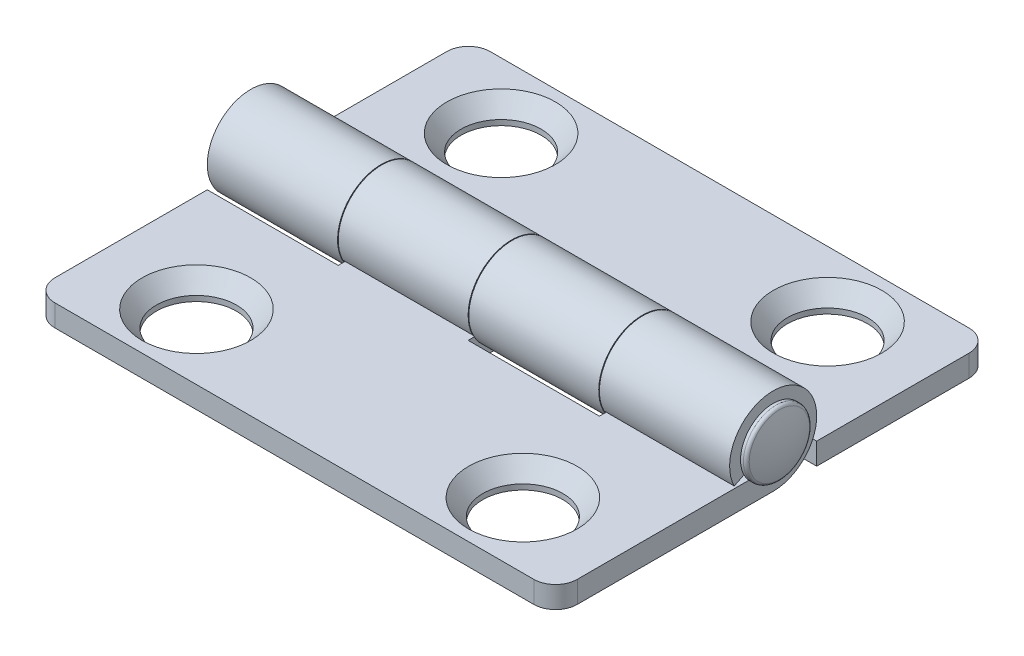
SolidWorks part; units mm, degrees
ref_plane "Front Plane" through (0, 0, 0) normal (0, 0, 1) x (1, 0, 0)
ref_plane "Top Plane" through (0, 0, 0) normal (0, 1, 0) x (1, 0, 0)
ref_plane "Right Plane" through (0, 0, 0) normal (1, 0, 0) x (0, 0, -1)
sketch "Sketch1" plane through (0, 0, 0) normal (0, 1, 0) x (1, 0, 0)
  line L0 (-19.05, 0) -> (19.05, 0) construction
  line L1 (-19.05, -15.875) -> (-19.05, 15.875) construction
  line L2 (11.9062, 11.1125) -> (11.9062, -11.1125) construction
  line L3 (-11.9062, -15.875) -> (11.9063, -15.875) construction
  line L4 (0, 0) -> (0, -15.875) construction
  line L5 (11.9062, -8.1915) -> (11.9063, -14.0335) construction
  line L7 (-11.9062, 11.1125) -> (11.9062, 11.1125) construction
  line L8 (-11.9062, 11.1125) -> (-11.9062, -11.1125) construction
  line L9 (-11.9062, -11.1125) -> (11.9062, -11.1125) construction
  line L10 (11.9062, 11.1125) -> (11.9062, -11.1125) construction
  line L11 (14.8273, -11.1125) -> (8.9853, -11.1125) construction
  line L12 (-11.9062, 11.1125) -> (11.9062, -11.1125) construction
  line L13 (-11.9062, -11.1125) -> (11.9062, 11.1125) construction
  circle A0 centre (11.9062, -11.1125) radius 3.9624 construction
  point P4 (0, 0)
  point P8 (-19.05, 0)
  point P17 (-9.525, 0)
  point P21 (11.9062, -11.1125)
  point P25 (11.9063, 0)
  point P26 (11.9062, -11.1125)
  point P38 (11.9062, -11.1125)
  dimension "Screw Head Diameter" = 7.9248
  dimension "Door Leaf Height" = 38.1
  dimension "Overall Width" = 31.75
  dimension "Hole Spacing" = 23.8125
  dimension "Knuckle Length" = 9.525
  dimension "Hole Diameter" = 5.842
  dimension "Hole Spacing 2" = 22.225
  dimension "Frame Leaf Height" = 38.1
  dimension "Door Leaf Width" = 15.875
  dimension "Frame Leaf Width" = 15.875
sketch "Sketch2" plane through (0, 0, 0) normal (1, 0, 0) x (0, 0, -1)
  line L2 (0, -3.175) -> (0, -1.5875) construction
  line L4 (0, 1.5875) -> (0, -1.5875) construction
  point P8 (0, 0)
  dimension "Leaf Thickness" = 1.5875
  dimension "Pin Diameter" = 3.175
sketch "Sketch3" plane through (0, 0, 0) normal (1, 0, 0) x (0, 0, -1)
  line L3 (0, 0) -> (-3.175, -1.5875) construction
  line L4 (0, -3.175) -> (-15.875, -3.175)
  line L5 (-15.875, -3.175) -> (-15.875, -1.5875)
  line L7 (-15.875, -1.5875) -> (0, -1.5875)
  line L8 (-15.875, 0) -> (15.875, 0) construction
  line L9 (-1.4199, -0.71) -> (-2.8398, -1.4199)
  line L11 (-3.175, 0) -> (-3.175, -1.5875) construction
  circle A4 centre (0, 0) radius 1.5875 construction
  circle A5 centre (0, 0) radius 3.175 construction
  arc A8 (-1.4199, -0.71) -> (0, -1.5875) centre (0, 0) cw
  arc A9 (-2.8398, -1.4199) -> (0, -3.175) centre (0, 0) cw
  point P0 (-2.8398, -1.4199)
  point P13 (-1.4199, -0.71)
extrude "Boss-Extrude1" add sketch "Sketch3" along normal mid plane 38.1
sketch "Sketch4" plane through (0, 0, 0) normal (0, 1, 0) x (1, 0, 0)
  line L0 (-19.05, -3.175) -> (19.05, -3.175) construction
  line L1 (-19.05, -3.175) -> (19.05, -3.175) construction
  line L2 (19.05, 3.175) -> (-19.05, 3.175) construction
  line L3 (19.05, 3.175) -> (-19.05, 3.175) construction
  line L4 (0, -3.175) -> (0, 3.175)
  line L6 (0, 3.175) -> (9.525, 3.175)
  line L7 (9.525, -3.175) -> (0, -3.175)
  line L8 (9.525, 3.175) -> (9.525, -3.175)
  point P8 (-9.525, 0)
  dimension "D1" = 9.525
extrude "Cut-Extrude1" cut sketch "Sketch4" against normal through all both and the other way through all
pattern_linear "LPattern1" count 2 spacing 19.05 along (-1, 0, 0) of "Cut-Extrude1"
sketch "Sketch5" plane through (0, -1.5875, 0) normal (0, 1, 0) x (1, 0, 0)
  line L0 (-9.525, -3.175) -> (0, -3.175) construction
  line L1 (-9.525, 3.175) -> (-9.4996, 3.175)
  line L2 (-9.525, 3.175) -> (-9.525, -3.175)
  line L3 (-9.525, -3.175) -> (-9.4996, -3.175)
  line L4 (-9.4996, 3.175) -> (-9.4996, -3.175)
  line L5 (9.525, 3.175) -> (9.525, -3.175) construction
  line L6 (0, 3.175) -> (-0.0254, 3.175)
  line L7 (0, 3.175) -> (0, -3.175)
  line L8 (0, -3.175) -> (-0.0254, -3.175)
  line L9 (-0.0254, 3.175) -> (-0.0254, -3.175)
  line L10 (9.525, 3.175) -> (9.5504, 3.175)
  line L11 (9.525, 3.175) -> (9.525, -3.175)
  line L12 (9.525, -3.175) -> (9.5504, -3.175)
  line L13 (9.5504, 3.175) -> (9.5504, -3.175)
  line L14 (9.525, -3.175) -> (19.05, -3.175) construction
  line L15 (19.05, 3.175) -> (9.525, 3.175) construction
  dimension "D1" = 0.0254
extrude "Cut-Extrude2" cut sketch "Sketch5" against normal through all both and the other way through all
sketch "Sketch6" plane through (0, -1.5875, 0) normal (0, 1, 0) x (1, 0, 0)
  line L0 (11.9062, -11.1125) -> (-11.9062, -11.1125) construction
  line L1 (11.9062, -11.1125) -> (11.9063, -15.875) construction
  line L2 (-11.9062, -11.1125) -> (-11.9062, -15.875) construction
  line L3 (11.9062, -11.1125) -> (13.3668, -13.6422) construction
  circle A0 centre (11.9062, -11.1125) radius 2.921
  circle A3 centre (-11.9062, -11.1125) radius 2.921
  point P7 (13.3668, -13.6422)
  dimension "D1" = 30
extrude "Cut-Extrude3" cut sketch "Sketch6" against normal through all
sketch "Sketch7" plane through (0, -1.5875, 0) normal (0, 1, 0) x (1, 0, 0)
  circle A0 centre (-11.9062, -11.1125) radius 3.9624
  circle A1 centre (11.9062, -11.1125) radius 3.9624
  circle A2 centre (11.9062, -11.1125) radius 3.9624 construction
extrude "Cut-Extrude4" cut sketch "Sketch7" against normal through all draft 41
fillet "Fillet1" radius 1.5875 2 edges at (19.05, -2.3813, 15.875) (-19.05, -2.3813, 15.875)
pattern_circular "CirPattern1" count 2 over 360 about axis through (0, 0, 0) along (0, 1, 0) of bodies 111 107
sketch "Sketch8" plane through (0, 0, 0) normal (1, 0, 0) x (0, 0, -1)
  circle A0 centre (0, 0) radius 1.5875
  dimension "D1" = 3.175
extrude "Boss-Extrude2" add sketch "Sketch8" along normal mid plane 38.1 separate body
sketch "Sketch9" plane through (0, 0, 0) normal (0, 0, 1) x (1, 0, 0)
  line L0 (-19.05, 0) -> (19.05, 0) construction
  line L2 (19.05, 2.3813) -> (19.05, -2.3813) construction
  line L3 (19.05, 0) -> (19.8437, 0) construction
  line L7 (19.05, 2.3813) -> (19.05, 0)
  line L8 (19.05, 0) -> (19.8437, 0)
  line L9 (19.05, -1.5875) -> (19.05, -3.175) construction
  line L10 (-19.05, -2.3813) -> (19.05, -2.3813) construction
  line L12 (19.05, 2.3813) -> (19.263, 2.3813)
  line L13 (19.05, 1.5875) -> (19.05, 3.175) construction
  line L15 (0, -2.3813) -> (0, 3.175) construction
  line L17 (-19.05, 0) -> (-19.8437, 0) construction
  line L18 (-19.05, 2.3813) -> (-19.263, 2.3813)
  line L19 (-19.05, 0) -> (-19.8437, 0)
  line L20 (-19.05, 2.3813) -> (-19.05, 0)
  line L21 (19.05, 1.5875) -> (9.5504, 1.5875) construction
  line L22 (19.05, 3.175) -> (9.5504, 3.175) construction
  line L23 (9.4996, 3.175) -> (0.0254, 3.175) construction
  arc A0 (19.05, 2.3813) -> (19.05, -2.3813) centre (15.875, 0) cw construction
  arc A4 (19.5053, 2.2035) -> (19.8437, 0) centre (12.5016, 0) cw
  arc A5 (19.263, 2.3813) -> (19.5053, 2.2035) centre (19.263, 2.1273) cw
  arc A6 (-19.263, 2.3813) -> (-19.5053, 2.2035) centre (-19.263, 2.1273) ccw
  arc A7 (-19.5053, 2.2035) -> (-19.8437, 0) centre (-12.5016, 0) ccw
  point P12 (19.05, 0)
  point P20 (19.4469, 0)
  point P29 (19.4469, 2.3813)
  point P34 (-19.4469, 2.3813)
  point P35 (-19.4469, 0)
  point P36 (19.05, 2.3813)
  dimension "D2" = 0.254
  dimension "D1" = 0.7937
revolve "Revolve1" add sketch "Sketch9" angle 360 about L0
equation "\"D1@Boss-Extrude1\" = \"Door Leaf Height@Sketch1\""
equation "\"D1@Sketch4\"=\"Knuckle Length@Sketch1\""
equation "\"D3@LPattern1\"=\"Knuckle Length@Sketch1\"*2"
equation "\"D1@Sketch8\" = \"Pin Diameter@Sketch2\""
equation "\"D1@Boss-Extrude2\" = \"Door Leaf Height@Sketch1\""
